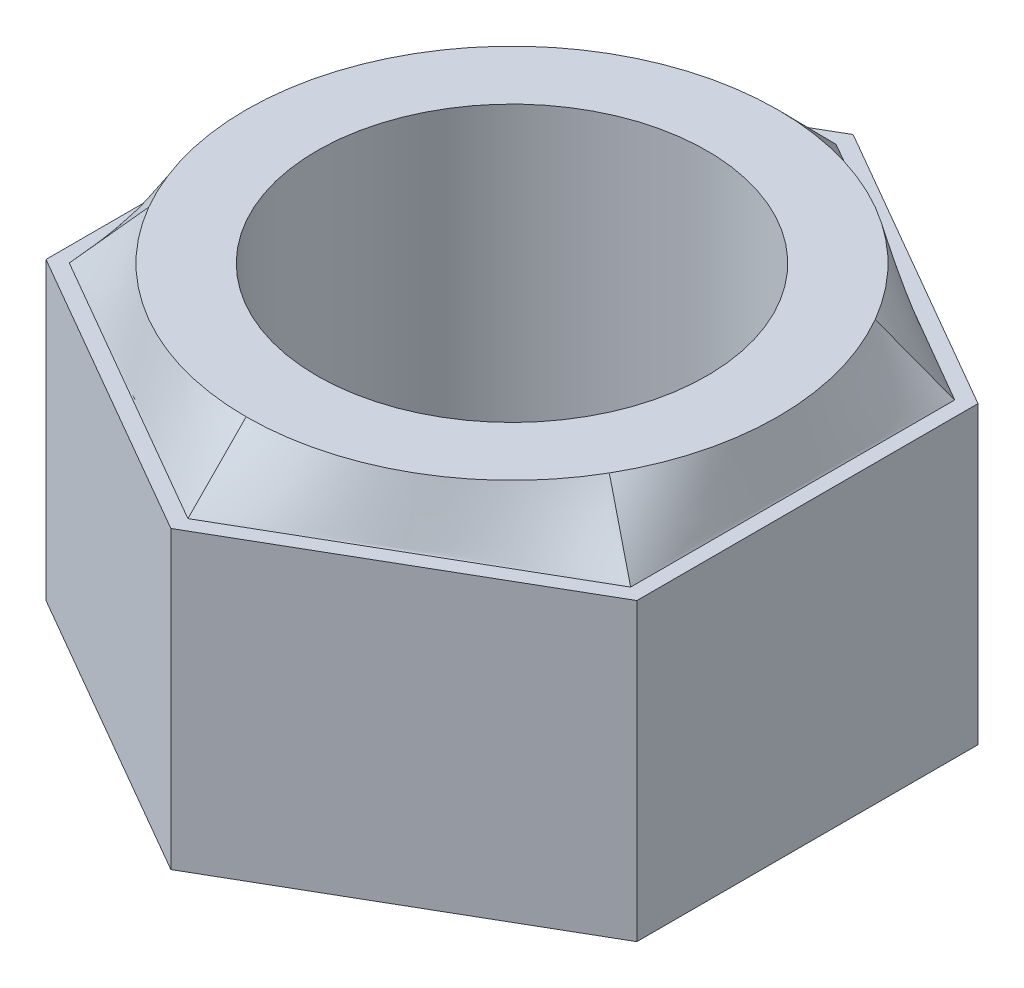
SolidWorks part; units mm, degrees
ref_plane "Front Plane" through (0, 0, 0) normal (0, 0, 1) x (1, 0, 0)
ref_plane "Top Plane" through (0, 0, 0) normal (0, 1, 0) x (1, 0, 0)
ref_plane "Right Plane" through (0, 0, 0) normal (1, 0, 0) x (0, 0, -1)
sketch "Sketch1" plane through (0, 0, 0) normal (0, 1, 0) x (1, 0, 0)
  line L1 (0, 5.7735) -> (-5, 2.8868)
  line L2 (-5, 2.8868) -> (-5, -2.8868)
  line L3 (-5, -2.8868) -> (0, -5.7735)
  line L4 (0, -5.7735) -> (5, -2.8868)
  line L5 (5, -2.8868) -> (5, 2.8868)
  line L6 (5, 2.8868) -> (0, 5.7735)
  circle A0 centre (0, 0) radius 5 construction
  dimension "D1" = 10
extrude "Body" add sketch "Sketch1" along normal blind 5
ref_plane "Plane1" through (0, 6, 0) normal (0, 1, 0) x (1, 0, 0)
sketch "Sketch4" plane through (0, 6, 0) normal (0, 1, 0) x (1, 0, 0)
  circle A2 centre (0, 0) radius 4.5
  dimension "D1" = 9
sketch "Sketch5" plane through (0, 5, 0) normal (0, 1, 0) x (1, 0, 0)
  line L12 (4.75, 2.7424) -> (0, 5.4848)
  line L13 (0, 5.4848) -> (-4.75, 2.7424)
  line L14 (-4.75, 2.7424) -> (-4.75, -2.7424)
  line L15 (-4.75, -2.7424) -> (0, -5.4848)
  line L16 (0, -5.4848) -> (4.75, -2.7424)
  line L17 (4.75, -2.7424) -> (4.75, 2.7424)
  line L18 (4.75, 2.7424) -> (0, 5.4848)
  line L19 (0, 5.4848) -> (-4.75, 2.7424)
  line L20 (-4.75, 2.7424) -> (-4.75, -2.7424)
  line L21 (-4.75, -2.7424) -> (0, -5.4848)
  line L22 (0, -5.4848) -> (4.75, -2.7424)
  line L23 (4.75, -2.7424) -> (4.75, 2.7424)
  dimension "D1" = 0.25
loft "Loft1" add profiles "Sketch5", "Sketch4"
hole_wizard "M6 Clearance Hole1" positions "Sketch6" profile "Sketch7" hole size "M6" standard "ANSI Metric" end condition through all
sketch "Sketch6" plane through (0, 6, 0) normal (0, 1, 0) x (1, 0, 0)
  point P0 (0, 0)
sketch "Sketch7" plane through (0, 6, 0) normal (1, 0, 0) x (0, 0, 1)
  line L0 (0, 0) -> (0, 6)
  line L1 (0, 6) -> (3.3, 6)
  line L2 (3.3, 6) -> (3.3, 0)
  line L5 (3.3, 0) -> (0, 0)
  line L11 (0, -6.35) -> (0, 107.95) construction
  dimension "Thru Hole Dia." = 6.6
  dimension "Thru Hole Depth" = 6
